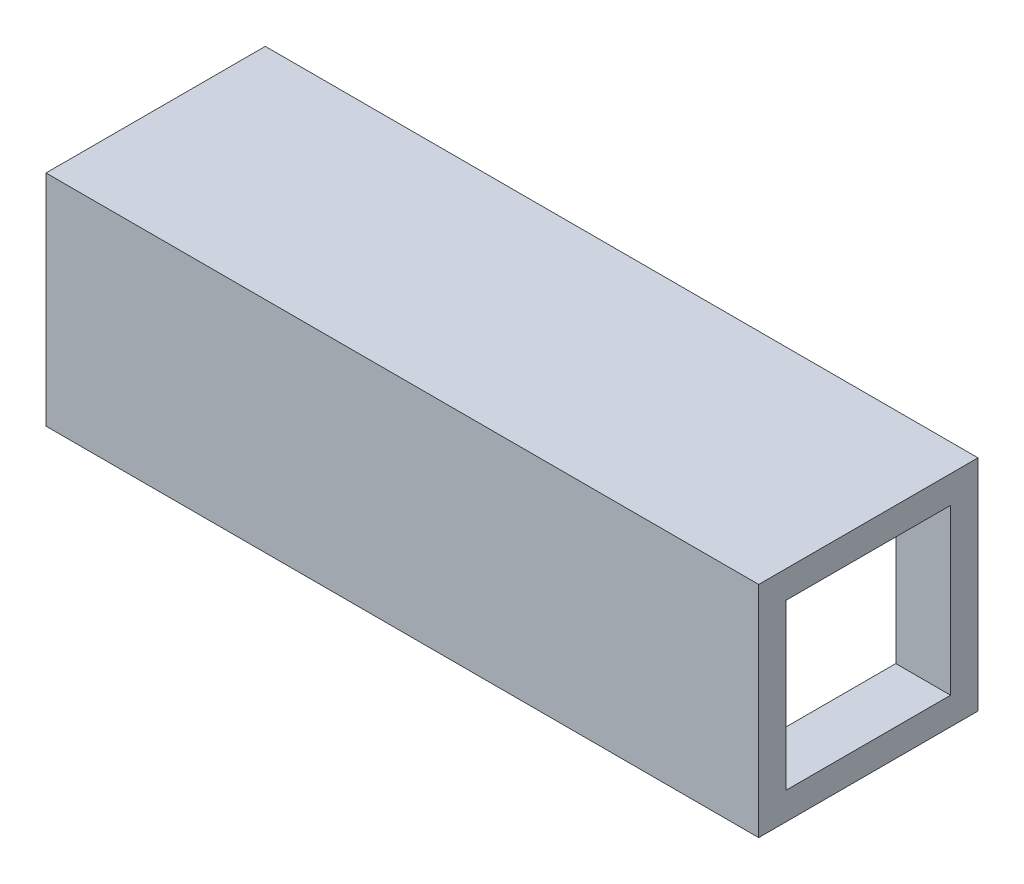
SolidWorks part; units mm, degrees
ref_plane "Front Plane" through (0, 0, 0) normal (0, 0, 1) x (1, 0, 0)
ref_plane "Top Plane" through (0, 0, 0) normal (0, 1, 0) x (1, 0, 0)
ref_plane "Right Plane" through (0, 0, 0) normal (1, 0, 0) x (0, 0, -1)
sketch "Sketch2" plane through (0, 0, 0) normal (1, 0, 0) x (0, 0, -1)
  line L0 (-9.525, 9.525) -> (9.525, 9.525)
  line L1 (-12.7, -12.7) -> (12.7, -12.7)
  line L2 (-12.7, -12.7) -> (-12.7, 12.7)
  line L3 (-12.7, 12.7) -> (12.7, 12.7)
  line L4 (12.7, -12.7) -> (12.7, 12.7)
  line L5 (-12.7, -12.7) -> (12.7, 12.7) construction
  line L6 (-12.7, 12.7) -> (12.7, -12.7) construction
  line L7 (9.525, -9.525) -> (9.525, 9.525)
  line L8 (-9.525, -9.525) -> (9.525, -9.525)
  line L9 (-9.525, -9.525) -> (-9.525, 9.525)
  point P0 (0, 0)
  dimension "D1" = 25.4
  dimension "D2" = 3.175
extrude "Boss-Extrude1" add sketch "Sketch2" along normal blind 82.55
sketch "Sketch3" plane through (0, 0, -12.7) normal (0, 0, -1) x (-1, 0, 0)
  line L0 (-82.55, -12.7) -> (0, -12.7) construction
  line L1 (-76.2, -12.7) -> (-48.26, -12.7)
  line L2 (-76.2, -12.7) -> (-76.2, 9.525)
  line L3 (-76.2, 9.525) -> (-48.26, 9.525)
  line L4 (-48.26, -12.7) -> (-48.26, 9.525)
  line L5 (-82.55, -12.7) -> (-82.55, 12.7) construction
  line L6 (-82.55, 12.7) -> (0, 12.7) construction
  dimension "D1" = 27.94
  dimension "D2" = 6.35
  dimension "D3" = 3.175
extrude "Cut-Extrude1" cut sketch "Sketch3" against normal up to surface (22.225 mm away) up to face at (41.275, 0, 9.525)
